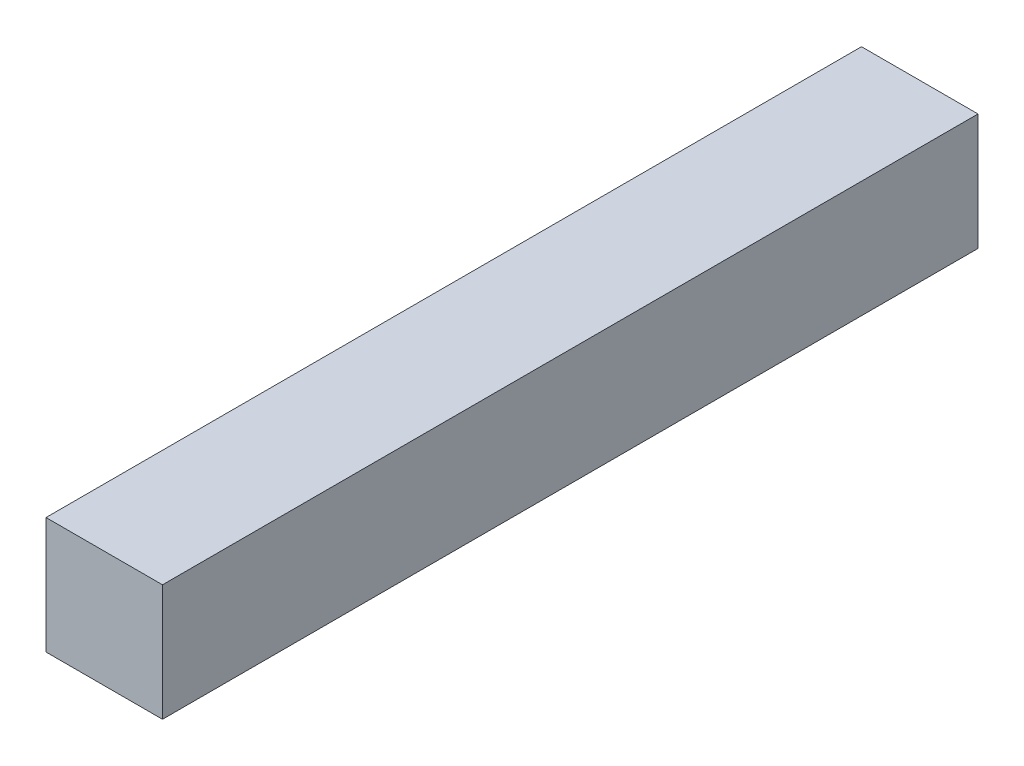
SolidWorks part; units mm, degrees
ref_plane "Plan de face" through (0, 0, 0) normal (0, 0, 1) x (1, 0, 0)
ref_plane "Plan de dessus" through (0, 0, 0) normal (0, 1, 0) x (1, 0, 0)
ref_plane "Plan de droite" through (0, 0, 0) normal (1, 0, 0) x (0, 0, -1)
sketch "Esquisse1" plane through (0, 0, 0) normal (0, 0, 1) x (1, 0, 0)
  line L1 (0, 0) -> (10, 0)
  line L2 (0, 0) -> (0, 10)
  line L3 (0, 10) -> (10, 10)
  line L4 (10, 0) -> (10, 10)
  dimension "D1" = 10
  dimension "D2" = 10
extrude "Boss.-Extru.1" add sketch "Esquisse1" along normal blind 70
